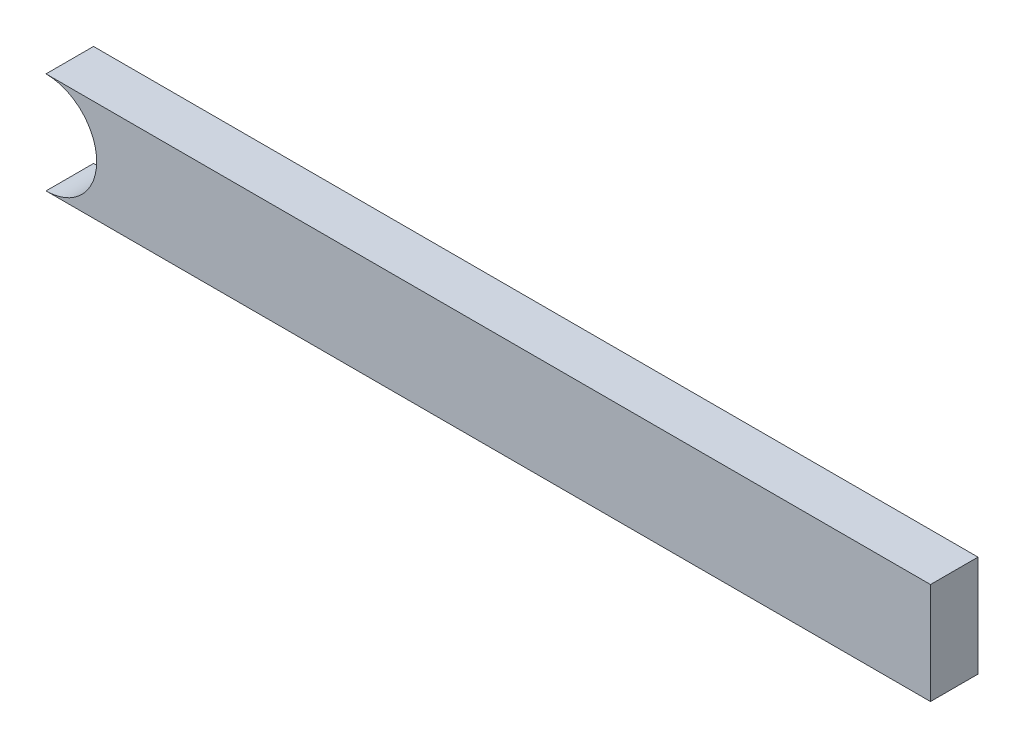
SolidWorks part; units mm, degrees
ref_plane "Front Plane" through (0, 0, 0) normal (0, 0, 1) x (1, 0, 0)
ref_plane "Top Plane" through (0, 0, 0) normal (0, 1, 0) x (1, 0, 0)
ref_plane "Right Plane" through (0, 0, 0) normal (1, 0, 0) x (0, 0, -1)
sketch "Sketch1" plane through (0, 0, 0) normal (0, 0, 1) x (1, 0, 0)
  line L1 (27.9239, -3.2) -> (-27.9239, -3.2)
  line L2 (27.9239, -3.2) -> (27.9239, 3.2)
  line L3 (27.9239, 3.2) -> (-27.9239, 3.2)
  line L5 (27.9239, -3.2) -> (-27.9239, 3.2) construction
  line L6 (27.9239, 3.2) -> (-27.9239, -3.2) construction
  arc A0 (-27.9239, 3.2) -> (-27.9239, -3.2) centre (-27.9239, 0) cw
  point P0 (0, 0)
  dimension "D1" = 6.4
extrude "Boss-Extrude1" add sketch "Sketch1" along normal blind 3
